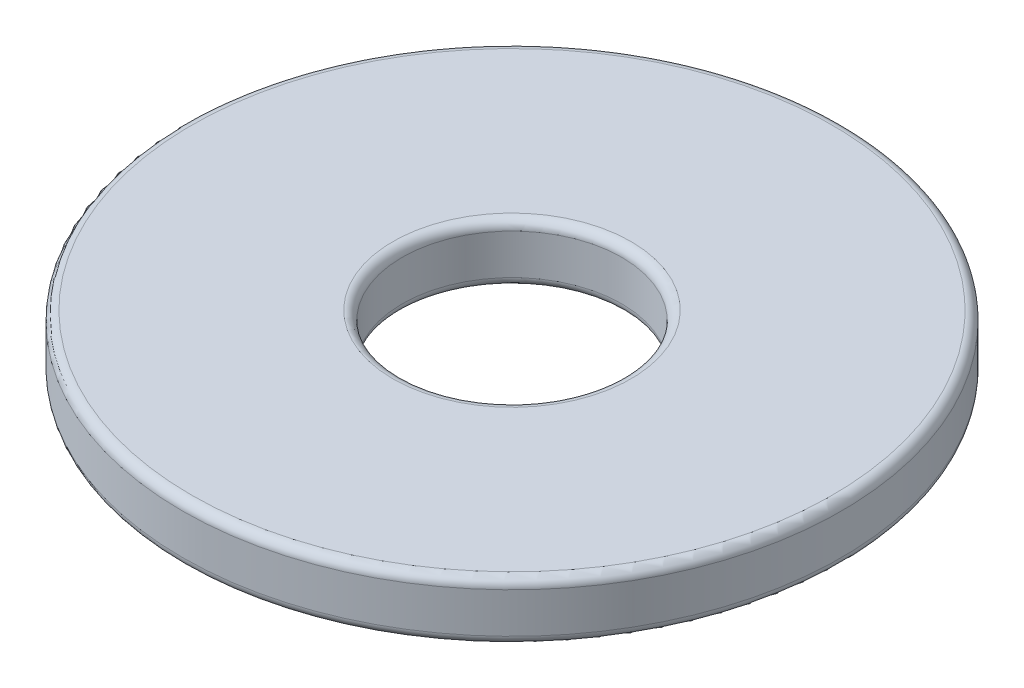
SolidWorks part; units mm, degrees
material "6061-T6 (SS)"
ref_plane "Front Plane" through (0, 0, 0) normal (0, 0, 1) x (1, 0, 0)
ref_plane "Top Plane" through (0, 0, 0) normal (0, 1, 0) x (1, 0, 0)
ref_plane "Right Plane" through (0, 0, 0) normal (1, 0, 0) x (0, 0, -1)
sketch "Sketch1" plane through (0, 0, 0) normal (0, 1, 0) x (1, 0, 0)
  circle A0 centre (0, 0) radius 3
  circle A1 centre (0, 0) radius 9
  dimension "D1" = 18
  dimension "D2" = 6
extrude "Boss-Extrude1" add sketch "Sketch1" along normal blind 1.6
fillet "Fillet1" radius 0.25 4 edges at (0, 0, 3) (0, 0, 9) (0, 1.6, 3) (0, 1.6, 9)
